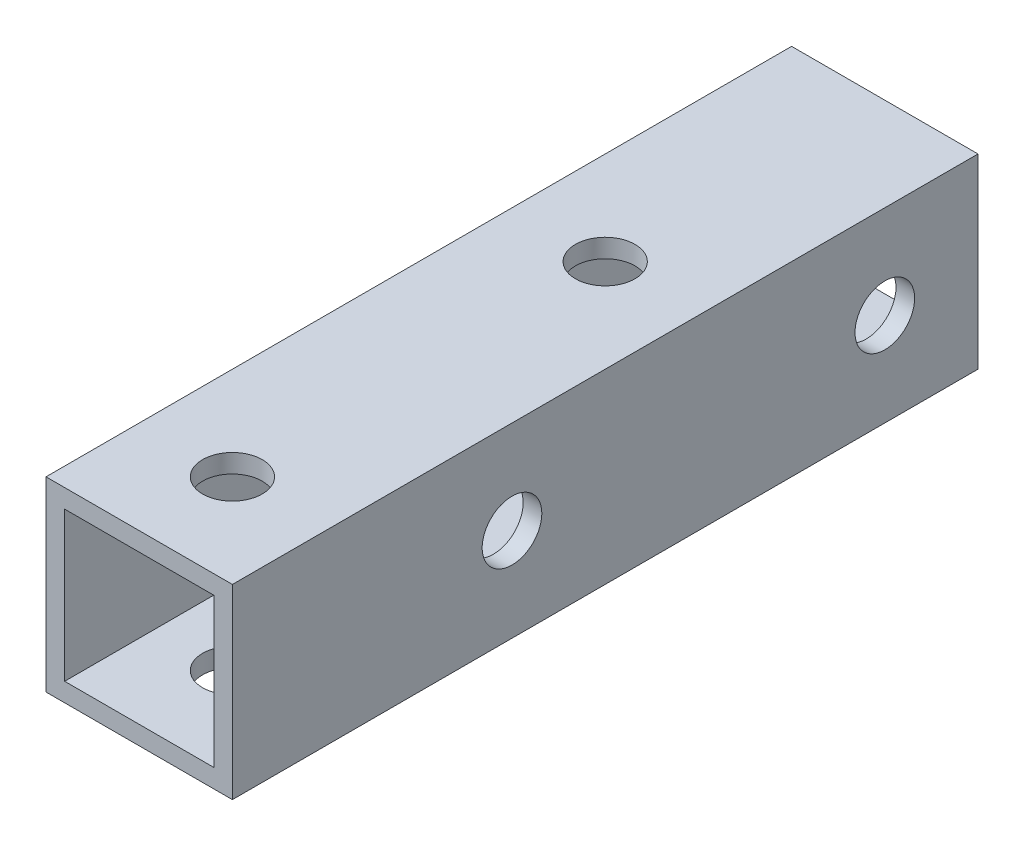
SolidWorks part; units mm, degrees
material "6061 合金"
ref_plane "正面" through (0, 0, 0) normal (0, 0, 1) x (1, 0, 0)
ref_plane "平面" through (0, 0, 0) normal (0, 1, 0) x (1, 0, 0)
ref_plane "右側面" through (0, 0, 0) normal (1, 0, 0) x (0, 0, -1)
sketch "断面 スケッチ" plane through (0, 0, 0) normal (0, 0, 1) x (1, 0, 0)
  line L1 (-5, -5) -> (5, -5)
  line L2 (-5, -5) -> (-5, 5)
  line L3 (-5, 5) -> (5, 5)
  line L4 (5, -5) -> (5, 5)
  line L5 (-5, -5) -> (5, 5) construction
  line L6 (-5, 5) -> (5, -5) construction
  point P0 (0, 0)
  dimension "D1" = 10
extrude "フレーム全長" add sketch "断面 スケッチ" along normal blind 40 thin thin type one direction reverse wall 1
sketch "上面穴 スケッチ" plane through (0, 5, 0) normal (0, 1, 0) x (1, 0, 0)
  line L0 (0, 0) -> (0, -40) construction
  line L1 (5, 0) -> (-5, 0) construction
  line L2 (5, -40) -> (-5, -40) construction
  line L3 (-5, -20) -> (5, -20) construction
  line L4 (-5, -40) -> (-5, 0) construction
  line L5 (5, -40) -> (5, 0) construction
  circle A0 centre (0, -15) radius 1.6
  circle A1 centre (0, -35) radius 1.6
  dimension "D1" = 5
  dimension "D2" = 3.2
  dimension "D3" = 20
  dimension "D4" = 3.2
sketch "側面穴 スケッチ" plane through (5, 0, 0) normal (1, 0, 0) x (0, 0, -1)
  line L0 (0, 0) -> (-40, 0) construction
  line L1 (0, -5) -> (0, 5) construction
  line L2 (-40, -5) -> (-40, 5) construction
  line L3 (-20, 5) -> (-20, -5) construction
  line L4 (-40, 5) -> (0, 5) construction
  line L5 (-40, -5) -> (0, -5) construction
  circle A0 centre (-5, 0) radius 1.6
  circle A1 centre (-25, 0) radius 1.6
  dimension "D1" = 5
  dimension "D2" = 3.2
  dimension "D3" = 20
extrude "上面穴貫通" cut sketch "上面穴 スケッチ" against normal through all
extrude "側面穴貫通" cut sketch "側面穴 スケッチ" against normal through all
fillet "フィレット" [suppressed] radius 5
